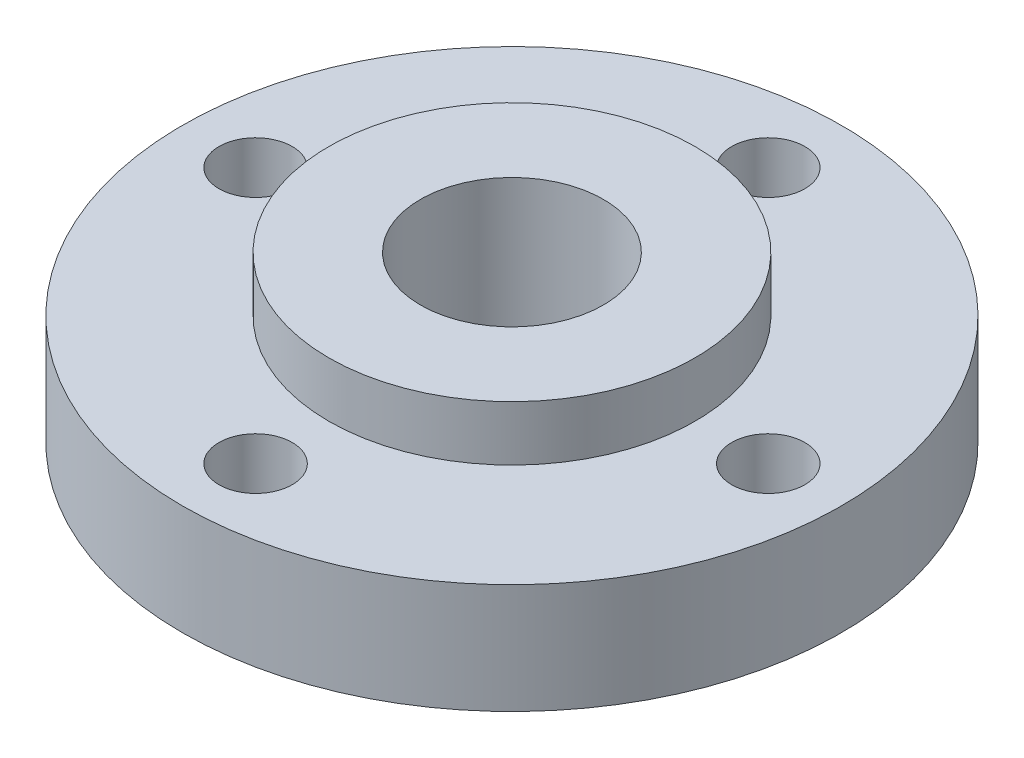
SolidWorks part; units mm, degrees
ref_plane "Front Plane" through (0, 0, 0) normal (0, 0, 1) x (1, 0, 0)
ref_plane "Top Plane" through (0, 0, 0) normal (0, 1, 0) x (1, 0, 0)
ref_plane "Right Plane" through (0, 0, 0) normal (1, 0, 0) x (0, 0, -1)
sketch "Sketch1" plane through (0, 0, 0) normal (0, 1, 0) x (1, 0, 0)
  circle A0 centre (0, 0) radius 36
  circle A1 centre (0, 0) radius 10
  dimension "D1" = 72
  dimension "D2" = 20
extrude "Boss-Extrude1" add sketch "Sketch1" along normal blind 12
sketch "Sketch2" plane through (0, 12, 0) normal (0, 1, 0) x (1, 0, 0)
  circle A0 centre (0, 0) radius 20
  circle A1 centre (0, 0) radius 10 construction
  circle A2 centre (0, 0) radius 10
  dimension "D1" = 40
extrude "Boss-Extrude2" add sketch "Sketch2" along normal blind 6
sketch "Sketch3" plane through (0, 12, 0) normal (0, 1, 0) x (1, 0, 0)
  circle A0 centre (0, 0) radius 28 construction
  circle A1 centre (0, -28) radius 4
  circle A2 centre (-28, 0) radius 4
  circle A3 centre (0, 28) radius 4
  circle A4 centre (28, 0) radius 4
  point P5 (0, 0)
  point P6 (0, 0)
  point P14 (0, 0)
  dimension "D1" = 56
  dimension "D2" = 8
  dimension "D3" = 4
extrude "Cut-Extrude1" cut sketch "Sketch3" against normal up to next
